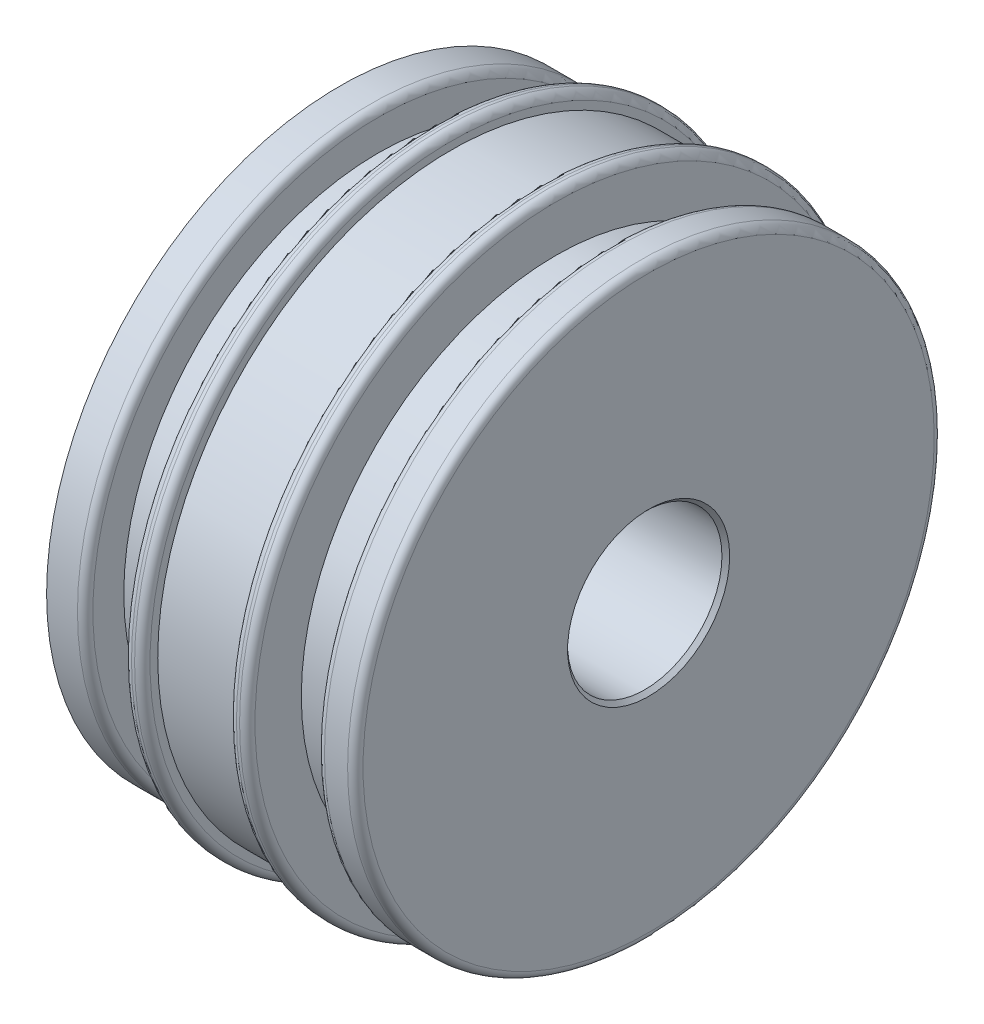
SolidWorks part; units mm, degrees
ref_plane "Alzado" through (0, 0, 0) normal (0, 0, 1) x (1, 0, 0)
ref_plane "Planta" through (0, 0, 0) normal (0, 1, 0) x (1, 0, 0)
ref_plane "Vista lateral" through (0, 0, 0) normal (1, 0, 0) x (0, 0, -1)
sketch "Sketch1" plane through (0, 0, 0) normal (0, 0, 1) x (1, 0, 0)
  line L2 (-67.3493, 19) -> (-69.8493, 19)
  line L3 (-69.8493, 19) -> (-69.8493, 16.5)
  line L4 (-69.8493, 16.5) -> (-73.3493, 16.5)
  line L5 (-73.3493, 16.5) -> (-73.3493, 20)
  line L9 (-80.1493, 19) -> (-80.1493, 20)
  line L10 (-80.1493, 20) -> (-81.3493, 20)
  line L11 (-81.3493, 20) -> (-81.3493, 16.5)
  line L12 (-81.3493, 16.5) -> (-84.8493, 16.5)
  line L13 (-84.8493, 16.5) -> (-84.8493, 19)
  line L14 (-84.8493, 19) -> (-87.3493, 19)
  line L18 (-67.3493, 5) -> (-67.3493, 19)
  line L19 (0, 0) -> (-91, 0) construction
  line L20 (-86.0526, 6) -> (-84.2084, 6)
  line L21 (-84.2084, 6) -> (-84.2084, 8)
  line L22 (-84.2084, 8) -> (-81.4084, 8)
  line L23 (-81.4084, 8) -> (-81.4084, 5)
  line L24 (-81.4084, 5) -> (-67.3493, 5)
  line L25 (-73.3493, 20) -> (-74.5493, 20)
  line L26 (-74.5493, 20) -> (-74.5493, 19)
  line L27 (-74.5493, 19) -> (-80.1493, 19)
  line L28 (-86.0526, 6) -> (-86.0526, 7.9579)
  line L29 (-86.0526, 7.9579) -> (-87.3493, 7.9579)
  line L30 (-87.3493, 19) -> (-87.3493, 7.9579)
  point P24 (-81.4084, 6.5)
  dimension "D2" = 5
  dimension "D3" = 16.5
  dimension "D4" = 3.5
  dimension "D5" = 6
  dimension "D6" = 3.5
  dimension "D7" = 16.5
  dimension "D8" = 5.6
  dimension "D9" = 1.2
  dimension "D10" = 2.8
  dimension "D11" = 19
  dimension "D12" = 2.5
  dimension "D13" = 2.5
  dimension "D14" = 20
  dimension "D15" = 20
  dimension "D16" = 19
  dimension "D17" = 19
  dimension "D18" = 8
  dimension "D19" = 1.2
  dimension "D20" = 7.9579
revolve "Revolución1" add sketch "Sketch1" angle 360 about L19
chamfer "Chaflán1" distance 0.25 angle 45 5 edges at (-81.4084, 0, -5) (-81.4084, 0, -8) (-67.3493, 0, -5) (-84.2084, 0, -6) (-84.2084, 0, -8)
fillet "Redondeo1" radius 0.5 7 edges at (-67.3493, 0, -19) (-69.8493, 0, -19) (-73.3493, 0, -20) (-74.5493, 0, -20) (-80.1493, 0, -20) (-81.3493, 0, -20) (-84.8493, 0, -19)
